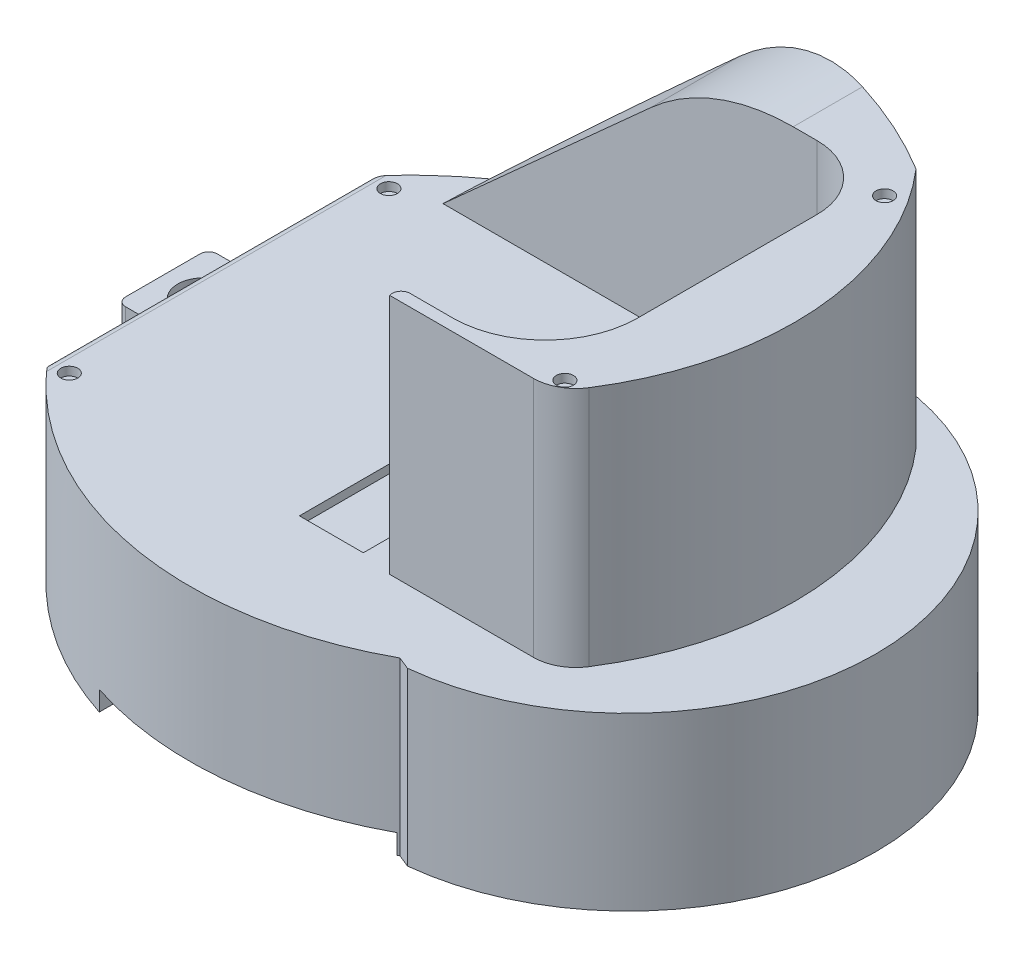
SolidWorks part; units mm, degrees
material "Chrome Stainless Steel"
ref_plane "Plano frontal" through (0, 0, 0) normal (0, 0, 1) x (1, 0, 0)
ref_plane "Plano superior" through (0, 0, 0) normal (0, 1, 0) x (1, 0, 0)
ref_plane "Plano direito" through (0, 0, 0) normal (1, 0, 0) x (0, 0, -1)
sketch "Sketch1" plane through (0, 0, 0) normal (0, 1, 0) x (1, 0, 0)
  line L0 (-1758.2654, 0) -> (3248.8911, 0) construction
  line L1 (0, 1091.3074) -> (0, -1250.298) construction
  line L2 (1046.3371, 577.8585) -> (1016.6673, 565.8707)
  line L3 (1046.3359, -577.8586) -> (1016.6658, -565.8716)
  line L4 (0, 375) -> (0, -375)
  arc A0 (1046.3371, 577.8585) -> (1046.3359, -577.8586) centre (986, 0) cw
  arc A1 (1016.6658, -565.8716) -> (66.7401, -445.8325) centre (624.2382, 147.288) cw
  arc A2 (1016.6673, 565.8707) -> (66.7401, 445.8325) centre (624.2382, -147.288) ccw
  arc A3 (66.7401, -445.8325) -> (2.6, -378.1514) centre (619.444, 142.1874) cw
  arc A4 (2.6, -378.1514) -> (0, -375) centre (145.5366, -257.5772) cw
  arc A5 (2.6, 378.1514) -> (0, 375) centre (145.5366, 257.5772) ccw
  arc A6 (66.7401, 445.8325) -> (2.6, 378.1514) centre (619.444, -142.1874) ccw
  point P8 (0, 0)
  point P16 (1567, -0.0006)
  dimension "D1" = 581
  dimension "D5" = 814
  dimension "D8" = 807
  dimension "D9" = 187
  dimension "D2" = 44
  dimension "D3" = 750
  dimension "D4" = 1567
  dimension "D6" = 32
  dimension "D7" = 32
extrude "Boss-Extrude1" add sketch "Sketch1" along normal blind 402 contours A2 A6 A5 L4 A4 A3 A1 L3 A0 L2
sketch "Sketch2" plane through (0, 0, 0) normal (0, 1, 0) x (1, 0, 0)
  line L0 (-612.5922, 0) -> (2089.703, 0) construction
  line L1 (144, 408) -> (1021.8907, 408)
  line L2 (834.8907, -408) -> (1171.8907, -408)
  line L3 (1171.8907, 258) -> (1171.8907, -163)
  line L4 (954.8907, -380) -> (854.6897, -380)
  arc A0 (1021.8907, 408) -> (1171.8907, 258) centre (1021.8907, 258) cw
  arc A1 (1171.8907, -163) -> (954.8907, -380) centre (954.8907, -163) cw
  arc A2 (1195.4402, 466.4828) -> (1256.2421, -361.7107) centre (670, 11.5789) cw
  arc A3 (185.9239, 467.2946) -> (446.1067, 595.7158) centre (565.0217, 27.0153) cw
  arc A4 (1171.8907, -408) -> (1256.2421, -361.7107) centre (1171.8907, -308) ccw
  arc A5 (446.1067, 595.7158) -> (1195.4402, 466.4828) centre (657.5338, -415.4161) cw
  arc A6 (185.9239, 467.2946) -> (144, 408) centre (283.7977, 353.6252) ccw
  arc A8 (834.8907, -408) -> (854.6897, -380) centre (854.6897, -401) cw
  dimension "D2" = 150
  dimension "D3" = 217
  dimension "D5" = 695
  dimension "D7" = 100
  dimension "D8" = 337
  dimension "D9" = 21
  dimension "D10" = 150
  dimension "D12" = 581
  dimension "D13" = 1033
  dimension "D1" = 816
  dimension "D4" = 421
  dimension "D6" = 1365
  dimension "D11" = 144
extrude "Boss-Extrude2" add sketch "Sketch2" along normal blind 969
sketch "Sketch3" plane through (0, 0, 0) normal (0, 0, 1) x (1, 0, 0)
  line L0 (144, 402) -> (773.7173, 969)
  line L3 (1021.8907, 402) -> (144, 402) construction
  line L4 (144, 969) -> (1021.8907, 969) construction
  line L5 (854.6897, 969) -> (833.6897, 969) construction
  line L6 (144, 402) -> (144, 969)
  line L7 (144, 969) -> (773.7173, 969)
  dimension "D2" = 42
extrude "Cut-Extrude1" cut sketch "Sketch3" against normal through all
fillet "Fillet1" radius 500 1 edges at (773.7173, 969, -509.5147)
sketch "Sketch4" plane through (0, 0, 0) normal (0, 1, 0) x (1, 0, 0)
  line L0 (-160.8723, 0) -> (1789.7556, 0) construction
  line L1 (610, -395) -> (760, -395)
  line L2 (610, -395) -> (610, 355)
  line L3 (610, 355) -> (760, 355)
  line L4 (760, -395) -> (760, 355)
  dimension "D1" = 150
  dimension "D2" = 395
  dimension "D3" = 750
  dimension "D4" = 610
extrude "Cut-Extrude2" cut sketch "Sketch4" against normal blind 20 from offset 402
sketch "Sketch7" plane through (0, 402, 0) normal (0, 1, 0) x (1, 0, 0)
  line L0 (0, 0) -> (494.2733, 0) construction
  line L1 (0, 375) -> (0, -375) construction
  circle A0 centre (50, 375) radius 20
  circle A1 centre (50, -375) radius 20
  dimension "D2" = 40
  dimension "D3" = 40
  dimension "D1" = 750
  dimension "D4" = 50
extrude "Cut-Extrude3" cut sketch "Sketch7" against normal blind 20
sketch "Sketch8" plane through (0, 969, 0) normal (0, 1, 0) x (1, 0, 0)
  line L0 (50, 375) -> (1352.977, 375) construction
  circle A0 centre (1213, 375) radius 20
  circle A1 centre (1213, -375) radius 20
  circle A2 centre (50, 375) radius 20 construction
  dimension "D1" = 1163
  dimension "D2" = 40
  dimension "D3" = 40
  dimension "D4" = 750
extrude "Cut-Extrude4" cut sketch "Sketch8" against normal blind 20
sketch "Sketch9" plane through (0, 0, 0) normal (0, 0, 1) x (1, 0, 0)
  line L0 (357, 0) -> (357, -28)
  line L1 (66.7401, 0) -> (1016.6658, 0) construction
  line L2 (357, -28) -> (-223, -28)
  line L3 (-223, -28) -> (-223, 17)
  line L4 (-223, 17) -> (-128, 17)
  line L5 (-128, 17) -> (-128, 173)
  line L6 (-128, 173) -> (-223, 173)
  line L7 (-223, 173) -> (-223, 218)
  line L8 (-223, 218) -> (0, 218)
  line L10 (0, 218) -> (0, 0)
  line L11 (0, 0) -> (357, 0)
  line L12 (357, 0) -> (355.5896, 1.8711)
  line L14 (0, 402) -> (0, 0) construction
  dimension "D1" = 223
  dimension "D2" = 28
  dimension "D3" = 580
  dimension "D4" = 357
  dimension "D5" = 246
  dimension "D6" = 156
  dimension "D7" = 45
  dimension "D8" = 95
extrude "Boss-Extrude3" add sketch "Sketch9" against normal blind 215 from offset 10 contours L11 L10 L8 L7 L6 L5 L4 L3 L2 L0 offset against normal yes
fillet "Fillet2" radius 20 4 edges at (-223, -5.5, -10) (-223, -5.5, -225) (-223, 195.5, -225) (-223, 195.5, -10)
sketch "Sketch10" plane through (0, 0, 0) normal (0, 1, 0) x (1, 0, 0)
  line L0 (-223, 117.5) -> (114.4269, 117.5) construction
  line L1 (-223, 205) -> (-223, 30) construction
  circle A0 centre (-128, 117.5) radius 60
  dimension "D2" = 120
  dimension "D1" = 95
extrude "Cut-Extrude5" cut sketch "Sketch10" along normal blind 226 and the other way through all
chamfer "Chamfer1" distance 50 angle 40 2 edges at (0, 0, -300) (0, 0, 182.5)
fillet "Fillet3" radius 20 1 edges at (0, 402, 0)
sketch "Sketch11" plane through (0, 0, 0) normal (0, 1, 0) x (1, 0, 0)
  circle A0 centre (687, 0) radius 315
  dimension "D1" = 630
  dimension "D2" = 687
extrude "Cut-Extrude6" cut sketch "Sketch11" along normal blind 66
sketch "Sketch12" plane through (0, 0, 0) normal (0, 0, 1) x (1, 0, 0)
  line L1 (372, 0) -> (1012, 0)
  line L2 (372, 0) -> (372, 46)
  line L3 (372, 46) -> (1012, 46)
  line L4 (1012, 0) -> (1012, 46)
  dimension "D1" = 46
  dimension "D2" = 640
extrude "Cut-Extrude7" cut sketch "Sketch12" against normal through all both and the other way through all
